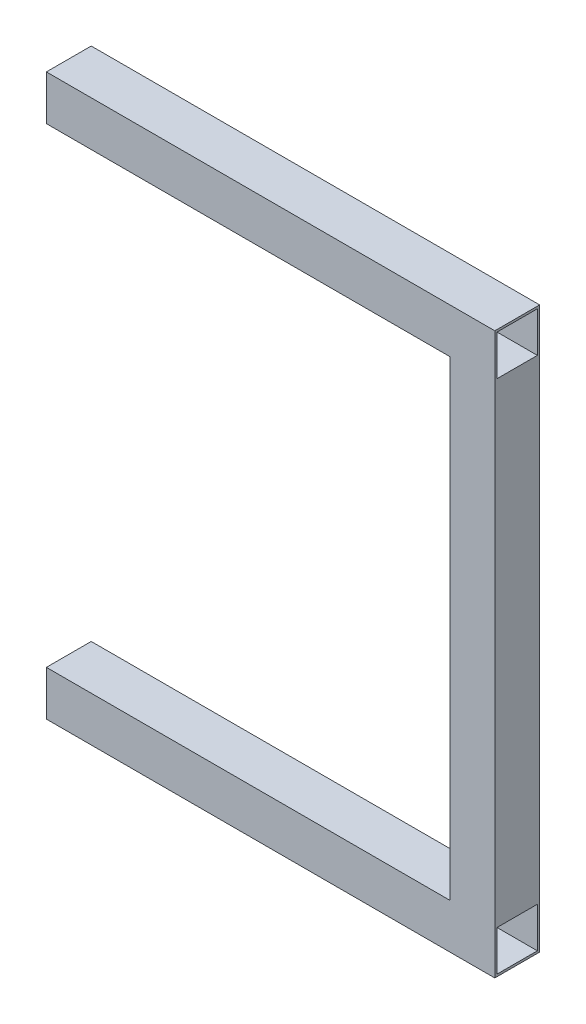
SolidWorks part; units mm, degrees
ref_plane "Front Plane" through (0, 0, 0) normal (0, 0, 1) x (1, 0, 0)
ref_plane "Top Plane" through (0, 0, 0) normal (0, 1, 0) x (1, 0, 0)
ref_plane "Right Plane" through (0, 0, 0) normal (1, 0, 0) x (0, 0, -1)
sketch "Sketch2" plane through (0, 0, 0) normal (0, 0, 1) x (1, 0, 0)
  line L0 (0, 0) -> (0, 40)
  line L1 (0, 40) -> (360, 40)
  line L2 (360, 40) -> (360, 460)
  line L3 (360, 460) -> (0, 460)
  line L4 (0, 460) -> (0, 500)
  line L5 (0, 500) -> (400, 500)
  line L6 (400, 500) -> (400, 0)
  line L7 (400, 0) -> (0, 0)
  dimension "D1" = 40
  dimension "D2" = 40
  dimension "D3" = 40
  dimension "D4" = 400
  dimension "D5" = 500
  dimension "D6" = 0
  dimension "D7" = 90
extrude "Boss-Extrude1" add sketch "Sketch2" along normal blind 40
sketch "Sketch3" plane through (0, 0, 0) normal (-1, 0, 0) x (0, 0, 1)
  line L0 (40, 500) -> (0, 500) construction
  line L1 (2, 498) -> (38, 498)
  line L2 (2, 498) -> (2, 462)
  line L3 (2, 462) -> (38, 462)
  line L4 (38, 498) -> (38, 462)
  line L5 (0, 500) -> (0, 460) construction
  line L6 (40, 460) -> (0, 460) construction
  line L7 (40, 500) -> (40, 460) construction
  dimension "D1" = 2
  dimension "D2" = 2
  dimension "D3" = 2
  dimension "D4" = 2
extrude "Cut-Extrude1" cut sketch "Sketch3" against normal blind 448
sketch "Sketch4" plane through (0, 0, 0) normal (-1, 0, 0) x (0, 0, 1)
  line L0 (40, 40) -> (0, 40) construction
  line L1 (2, 38) -> (38, 38)
  line L2 (2, 38) -> (2, 2)
  line L3 (2, 2) -> (38, 2)
  line L4 (38, 38) -> (38, 2)
  line L5 (0, 40) -> (0, 0) construction
  line L6 (40, 40) -> (40, 0) construction
  line L7 (40, 0) -> (0, 0) construction
  dimension "D1" = 2
  dimension "D2" = 2
  dimension "D3" = 2
  dimension "D4" = 2
extrude "Cut-Extrude2" cut sketch "Sketch4" against normal blind 448
